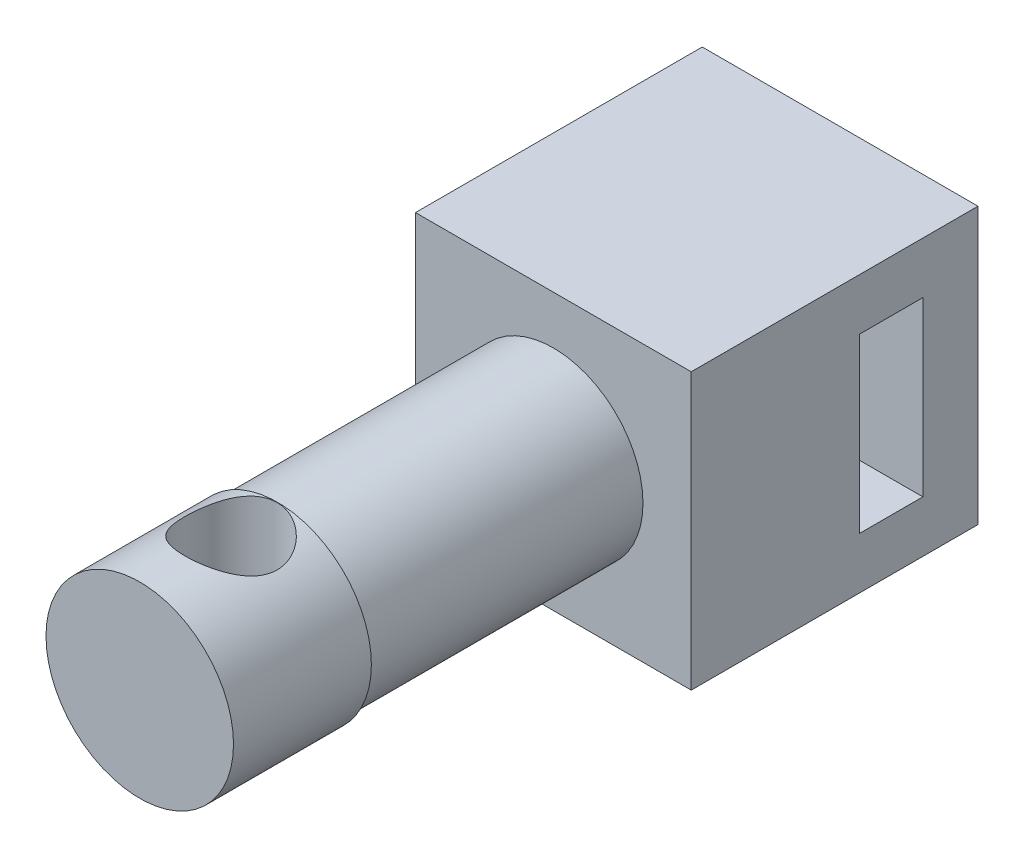
SolidWorks part; units mm, degrees
ref_plane "Front Plane" through (0, 0, 0) normal (0, 0, 1) x (1, 0, 0)
ref_plane "Top Plane" through (0, 0, 0) normal (0, 1, 0) x (1, 0, 0)
ref_plane "Right Plane" through (0, 0, 0) normal (1, 0, 0) x (0, 0, -1)
sketch "Sketch1" plane through (0, 0, 0) normal (0, 1, 0) x (1, 0, 0)
  line L1 (-5, -5) -> (5, -5)
  line L2 (-5, -5) -> (-5, 5)
  line L3 (-5, 5) -> (5, 5)
  line L4 (5, -5) -> (5, 5)
  line L5 (-5, -5) -> (5, 5) construction
  line L6 (-5, 5) -> (5, -5) construction
  point P0 (0, 0)
  dimension "D1" = 10
  dimension "D2" = 10
extrude "Boss-Extrude1" add sketch "Sketch1" along normal blind 5
sketch "Sketch2" plane through (0, 5, 0) normal (0, 1, 0) x (1, 0, 0)
  circle A0 centre (0, 0) radius 1.675
  dimension "D1" = 3.35
extrude "Cut-Extrude1" cut sketch "Sketch2" against normal through all both and the other way through all
sketch "Sketch3" plane through (0, 5, 0) normal (0, 1, 0) x (1, 0, 0)
  line L0 (-3.1292, 0) -> (-3.1292, -5)
  line L1 (3.1292, 0) -> (1.5646, 2.71)
  line L2 (1.5646, 2.71) -> (-1.5646, 2.71)
  line L3 (-1.5646, 2.71) -> (-3.1292, 0)
  line L4 (-3.1292, 0) -> (-1.5646, -2.71)
  line L5 (-1.5646, -2.71) -> (1.5646, -2.71)
  line L6 (1.5646, -2.71) -> (3.1292, 0)
  line L7 (-5, -5) -> (5, -5) construction
  line L8 (-3.1292, -5) -> (3.1292, -5)
  line L9 (3.1292, -5) -> (3.1292, 0)
  circle A0 centre (0, 0) radius 2.71 construction
  circle M7 centre (0, 0) radius 1.675
  line M11 (-5, -5) -> (5, -5)
  dimension "D1" = 5.42
extrude "Cut-Extrude3" cut sketch "Sketch3" against normal blind 2.3 contours L5 L6 L1 L2 L3 L4 M7 | L9 L6 L5 L4 L0 M11
sketch "Sketch4" plane through (0, 5, 0) normal (0, 1, 0) x (1, 0, 0)
  line L1 (-5, -5) -> (5, -5)
  line L2 (-5, -5) -> (-5, 5)
  line L3 (-5, 5) -> (5, 5)
  line L4 (5, -5) -> (5, 5)
extrude "Boss-Extrude2" add sketch "Sketch4" along normal blind 2.7
sketch "Sketch6" plane through (0, 7.7, 0) normal (0, 1, 0) x (1, 0, 0)
  line L1 (-5, -5) -> (5, -5)
  line L2 (-5, -5) -> (-5, 5)
  line L3 (-5, 5) -> (5, 5)
  line L4 (5, -5) -> (5, 5)
  line L5 (-5, -5) -> (5, 5) construction
  line L6 (-5, 5) -> (5, -5) construction
  point P0 (0, 0)
extrude "Boss-Extrude3" add sketch "Sketch6" along normal blind 7
sketch "Sketch9" plane through (0, 0, -5) normal (0, 0, -1) x (-1, 0, 0)
  line L0 (5, 14.7) -> (5, 0) construction
  line L1 (-5, 0) -> (5, 0)
  line L2 (-5, 0) -> (-5, 7.7)
  line L3 (-5, 7.7) -> (5, 7.7)
  line L4 (5, 0) -> (5, 7.7)
  circle A0 centre (0, 9.85) radius 2.15
  dimension "D2" = 4.3
  dimension "D1" = 7.7
  dimension "D3" = 2.15
extrude "Cut-Extrude12" cut sketch "Sketch9" against normal through all contours A0
sketch "Sketch10" plane through (0, 5, 0) normal (0, -1, 0) x (1, 0, 0)
  line L0 (-5, 5) -> (5, -5) construction
  circle A0 centre (0, 0) radius 1.675
  dimension "D1" = 3.35
extrude "Cut-Extrude13" cut sketch "Sketch10" against normal through all
sketch "Sketch11" plane through (0, 14.7, 0) normal (0, 1, 0) x (1, 0, 0)
  line L0 (-5, -5) -> (5, 5) construction
  line L1 (3.1292, 0) -> (1.5646, 2.71)
  line L2 (1.5646, 2.71) -> (-1.5646, 2.71)
  line L3 (-1.5646, 2.71) -> (-3.1292, 0)
  line L4 (-3.1292, 0) -> (-1.5646, -2.71)
  line L5 (-1.5646, -2.71) -> (1.5646, -2.71)
  line L6 (1.5646, -2.71) -> (3.1292, 0)
  line L7 (-3.1292, 0) -> (-3.1292, -5)
  line L8 (-3.1292, -5) -> (3.1292, -5)
  line L9 (-5, -5) -> (5, -5) construction
  line L10 (3.1292, -5) -> (3.1292, 0)
  line L11 (-3.1292, -5) -> (-5, -5)
  line L12 (-5, -5) -> (-5, 5)
  line L13 (-5, 5) -> (5, 5)
  line L14 (5, 5) -> (5, -5)
  line L15 (5, -5) -> (3.1292, -5)
  circle A0 centre (0, 0) radius 2.71 construction
  line M4 (5, -5) -> (5, 5)
  line M5 (5, 5) -> (-5, 5)
  line M6 (-5, 5) -> (-5, -5)
  line M7 (-5, -5) -> (5, -5)
  dimension "D1" = 5.42
extrude "Boss-Extrude4" add sketch "Sketch11" along normal blind 2.3 contours L10 L7 L3 L2 L1 M7 M4 M5 M6
sketch "Sketch12" plane through (0, 17, 0) normal (0, 1, 0) x (1, 0, 0)
  line L0 (-5, 5) -> (5, -5) construction
  line L1 (-5, -5) -> (5, -5)
  line L2 (-5, -5) -> (-5, 5)
  line L3 (-5, 5) -> (5, 5)
  line L4 (5, -5) -> (5, 5)
  line L5 (-5, -5) -> (5, 5) construction
  line L6 (-5, 5) -> (5, -5) construction
  point P0 (0, 0)
extrude "Boss-Extrude5" add sketch "Sketch12" along normal blind 2.7
sketch "Sketch13" plane through (0, 19.7, 0) normal (0, 1, 0) x (1, 0, 0)
  line L0 (-5, 5) -> (5, -5) construction
  circle A0 centre (0, 0) radius 1.675
  dimension "D1" = 3.35
extrude "Cut-Extrude14" cut sketch "Sketch13" against normal blind 2.7
sketch "Sketch14" plane through (0, 0, -5) normal (0, 0, -1) x (-1, 0, 0)
  line L0 (0, 7.7) -> (0, 12) construction
  circle A0 centre (0, 9.85) radius 2.15 construction
  circle A1 centre (0, 9.85) radius 2.15
  dimension "D1" = 4.3
extrude "Boss-Extrude6" add sketch "Sketch14" against normal blind 0.76 separate body
sketch "Sketch16" plane through (0, 0, 5) normal (0, 0, 1) x (1, 0, 0)
  line L0 (0, 0) -> (0, 19.7) construction
  line L1 (-5, 19.7) -> (5, 19.7) construction
  line L3 (-5, 0) -> (5, 0)
  line L4 (-5, 0) -> (-5, 19.7)
  line L5 (-5, 19.7) -> (5, 19.7)
  line L6 (5, 0) -> (5, 19.7)
  line L7 (-5, 0) -> (5, 19.7) construction
  line L8 (-5, 19.7) -> (5, 0) construction
  point P5 (0, 9.85)
extrude "Cut-Extrude15" cut sketch "Sketch16" against normal blind 2.29
sketch "Sketch17" plane through (0, 0, 0) normal (0, -1, 0) x (-1, 0, 0)
  line L0 (5, 5) -> (-5, -5) construction
  line L1 (5, -2.71) -> (-5, -2.71)
  line L2 (-5, -2.71) -> (-5, 5)
  line L3 (-5, 5) -> (5, 5)
  line L4 (5, 5) -> (5, -2.71)
  circle A0 centre (0, 0) radius 1.675
extrude "Boss-Extrude7" add sketch "Sketch17" along normal blind 1
sketch "Sketch18" plane through (0, 19.7, 0) normal (0, 1, 0) x (1, 0, 0)
  line L0 (-5, 5) -> (5, 5)
  line L1 (5, 5) -> (5, -2.71)
  line L2 (5, -2.71) -> (-5, -2.71)
  line L3 (-5, -2.71) -> (-5, 5)
  circle A0 centre (0, 0) radius 1.675
extrude "Boss-Extrude9" add sketch "Sketch18" along normal blind 1 contours L3 L0 L1 L2
sketch "Sketch22" plane through (0, 0, -5) normal (0, 0, -1) x (-1, 0, 0)
  line L0 (0, 12.9792) -> (-5, 12.9792)
  line L1 (0, 6.7208) -> (2.71, 8.2854)
  line L2 (2.71, 8.2854) -> (2.71, 11.4146)
  line L3 (2.71, 11.4146) -> (0, 12.9792)
  line L4 (0, 12.9792) -> (-2.71, 11.4146)
  line L5 (-2.71, 11.4146) -> (-2.71, 8.2854)
  line L6 (-2.71, 8.2854) -> (0, 6.7208)
  line L7 (-5, 4.85) -> (5, 4.85)
  line L8 (-5, 4.85) -> (-5, 14.85)
  line L9 (-5, 14.85) -> (5, 14.85)
  line L10 (5, 4.85) -> (5, 14.85)
  line L11 (-5, 4.85) -> (5, 14.85) construction
  line L12 (-5, 14.85) -> (5, 4.85) construction
  line L13 (0, 6.7208) -> (-5, 6.7208)
  circle A0 centre (0, 9.85) radius 2.71 construction
  dimension "D1" = 5.42
  dimension "D2" = 10
  dimension "D3" = 10
extrude "Boss-Extrude13" add sketch "Sketch22" along normal blind 2.3 contours L1 L13 L8 L7 L10 L9 L0 L3 L2
sketch "Sketch23" plane through (0, 0, -7.3) normal (0, 0, -1) x (-1, 0, 0)
  line L0 (-5, 14.85) -> (5, 4.85) construction
  line L1 (5, 14.85) -> (-5, 4.85) construction
  line L3 (-5, 4.85) -> (5, 4.85)
  line L4 (-5, 4.85) -> (-5, 14.85)
  line L5 (-5, 14.85) -> (5, 14.85)
  line L6 (5, 4.85) -> (5, 14.85)
  line L7 (-5, 4.85) -> (5, 14.85) construction
  line L8 (-5, 14.85) -> (5, 4.85) construction
  circle A0 centre (0, 9.85) radius 1.675
  point P8 (0, 9.85)
  dimension "D1" = 3.35
extrude "Boss-Extrude15" add sketch "Sketch23" along normal blind 2
sketch "Sketch24" plane through (0, 0, -9.3) normal (0, 0, -1) x (-1, 0, 0)
  line L1 (-5, 4.85) -> (5, 4.85)
  line L2 (-5, 4.85) -> (-5, 14.85)
  line L3 (-5, 14.85) -> (5, 14.85)
  line L4 (5, 4.85) -> (5, 14.85)
  line L5 (-5, 4.85) -> (5, 14.85) construction
  line L6 (-5, 14.85) -> (5, 4.85) construction
  line L7 (-5, -1) -> (5, -1)
  line L8 (-5, -1) -> (-5, 20.7)
  line L9 (-5, 20.7) -> (5, 20.7)
  line L10 (5, -1) -> (5, 20.7)
  line L11 (-5, -1) -> (5, 20.7) construction
  line L12 (-5, 20.7) -> (5, -1) construction
  point P0 (0, 9.85)
  point P7 (0, 9.85)
  line M1 (5, 14.85) -> (-5, 14.85)
  line M3 (-5, 4.85) -> (5, 4.85)
extrude "Cut-Extrude16" cut sketch "Sketch24" against normal through all contours L10 L9 L8 M1 | L7 L10 L8 M3
sketch "Sketch25" plane through (0, 0, 2.71) normal (0, 0, 1) x (1, 0, 0)
  line L1 (-5, 4.85) -> (5, 4.85)
  line L2 (-5, 4.85) -> (-5, 14.85)
  line L3 (-5, 14.85) -> (5, 14.85)
  line L4 (5, 4.85) -> (5, 14.85)
  line L5 (-5, 4.85) -> (5, 14.85) construction
  line L6 (-5, 14.85) -> (5, 4.85) construction
  point P0 (0, 9.85)
extrude "Boss-Extrude16" add sketch "Sketch25" against normal blind 6
sketch "Sketch26" plane through (0, 0, 2.71) normal (0, 0, 1) x (1, 0, 0)
  line L0 (-5, 4.85) -> (5, 14.85) construction
  line L2 (-5, 4.85) -> (5, 4.85)
  line L3 (-5, 4.85) -> (-5, 14.85)
  line L4 (-5, 14.85) -> (5, 14.85)
  line L5 (5, 4.85) -> (5, 14.85)
  line L6 (-5, 4.85) -> (5, 14.85) construction
  line L7 (-5, 14.85) -> (5, 4.85) construction
  point P4 (0, 9.85)
extrude "Cut-Extrude17" cut sketch "Sketch26" against normal up to surface (7.71 mm away) up to face at (0.7633, 9.85, -5)
sketch "Sketch27" plane through (0, 0, -5) normal (0, 0, 1) x (1, 0, 0)
  line L1 (-5, 4.85) -> (5, 4.85)
  line L2 (-5, 4.85) -> (-5, 14.85)
  line L3 (-5, 14.85) -> (5, 14.85)
  line L4 (5, 4.85) -> (5, 14.85)
  line L5 (-5, 4.85) -> (5, 14.85) construction
  line L6 (-5, 14.85) -> (5, 4.85) construction
  point P0 (0, 9.85)
extrude "Boss-Extrude17" add sketch "Sketch27" along normal blind 6.1
sketch "Sketch28" plane through (0, 0, 1.1) normal (0, 0, 1) x (1, 0, 0)
  line L0 (-5, 14.85) -> (5, 4.85) construction
  circle A0 centre (0, 9.85) radius 3.25
  dimension "D1" = 6.5
extrude "Boss-Extrude18" add sketch "Sketch28" along normal blind 10
sketch "Sketch29" plane through (0, 0, -5) normal (0, 0, -1) x (-1, 0, 0)
  circle A0 centre (0, 9.85) radius 1.625
  dimension "D1" = 3.25
extrude "Cut-Extrude18" cut sketch "Sketch29" against normal blind 2.7
sketch "Sketch33" plane through (0, 0, 11.1) normal (0, 0, 1) x (1, 0, 0)
  line L1 (-3.4, 6.45) -> (3.4, 6.45)
  line L2 (-3.4, 6.45) -> (-3.4, 13.25)
  line L3 (-3.4, 13.25) -> (3.4, 13.25)
  line L4 (3.4, 6.45) -> (3.4, 13.25)
  line L5 (-3.4, 6.45) -> (3.4, 13.25) construction
  line L6 (-3.4, 13.25) -> (3.4, 6.45) construction
  dimension "D2" = 6.8
  dimension "D3" = 6.8
extrude "Boss-Extrude19" add sketch "Sketch33" along normal blind 5
sketch "Sketch36" plane through (0, 6.45, 0) normal (0, -1, 0) x (-1, 0, 0)
  line L0 (3.4, -11.1) -> (-3.4, -11.1) construction
  circle A0 centre (0, -12.79) radius 1.675
  dimension "D1" = 3.35
  dimension "D2" = 1.69
extrude "Cut-Extrude22" cut sketch "Sketch36" against normal blind 10
sketch "Sketch37" plane through (0, 0, 16.1) normal (0, 0, 1) x (1, 0, 0)
  line L0 (-3.4, 13.25) -> (3.4, 6.45)
  line L1 (-3.4, 6.45) -> (3.4, 6.45) construction
  line L2 (-3.4, 13.25) -> (3.4, 13.25) construction
  line L3 (-3.4, 6.45) -> (3.4, 6.45)
  line L4 (-3.4, 6.45) -> (-3.4, 13.25)
  line L5 (-3.4, 13.25) -> (3.4, 13.25)
  line L6 (3.4, 6.45) -> (3.4, 13.25)
  line L7 (-3.4, 6.45) -> (3.4, 13.25) construction
  line L8 (-3.4, 13.25) -> (3.4, 6.45) construction
  line L9 (3.4, 6.45) -> (3.4, 13.25) construction
  circle A0 centre (0, 9.85) radius 3.4
  line M4 (-3.4, 6.45) -> (3.4, 6.45)
  line M5 (3.4, 6.45) -> (3.4, 13.25)
  line M6 (3.4, 13.25) -> (-3.4, 13.25)
  line M7 (-3.4, 13.25) -> (-3.4, 6.45)
  dimension "D1" = 6.8
extrude "Cut-Extrude23" cut sketch "Sketch37" against normal blind 10 contours A0 L5 L0 | A0 L0 M7 | A0 L4 M4 | A0 L3 L0 | A0 L0 M5 | A0 L6 M6
